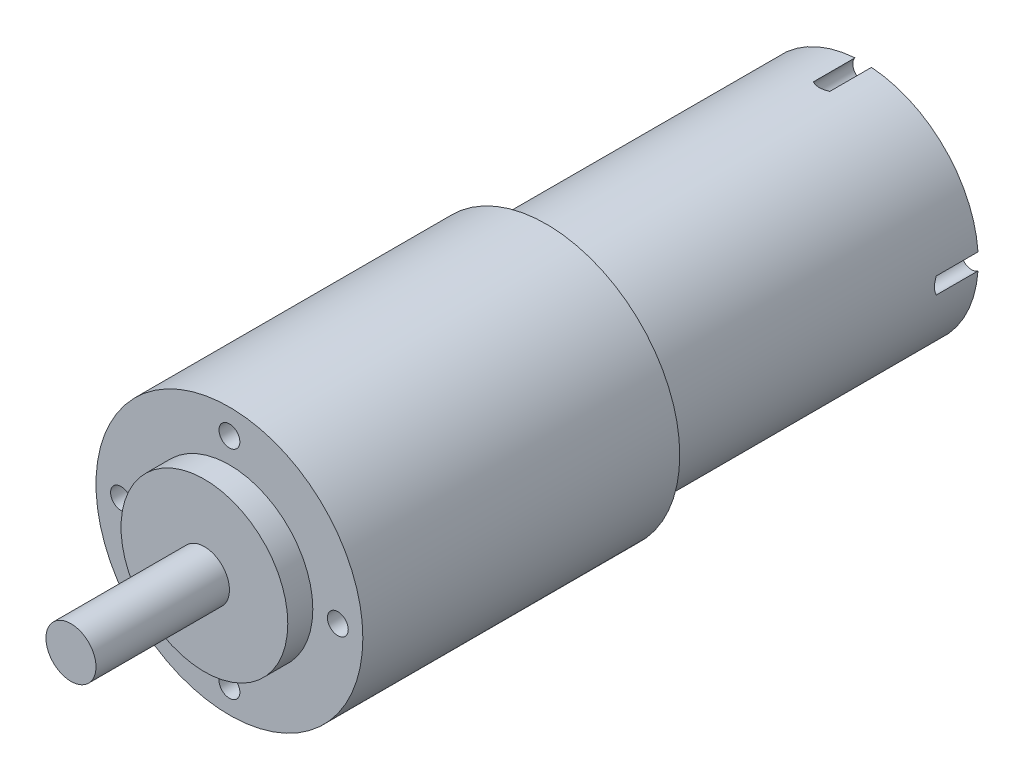
SolidWorks part; units mm, degrees
ref_plane "Front Plane" through (0, 0, 0) normal (0, 0, 1) x (1, 0, 0)
ref_plane "Top Plane" through (0, 0, 0) normal (0, 1, 0) x (1, 0, 0)
ref_plane "Right Plane" through (0, 0, 0) normal (1, 0, 0) x (0, 0, -1)
sketch "Sketch1" plane through (0, 0, 0) normal (0, 0, 1) x (1, 0, 0)
  circle A0 centre (0, 0) radius 16
  dimension "D1" = 32
extrude "Boss-Extrude1" add sketch "Sketch1" along normal blind 38 contours A0
sketch "Sketch2" plane through (0, 0, 0) normal (0, 0, -1) x (-1, 0, 0)
  circle A0 centre (0, 0) radius 13.8
  dimension "D1" = 27.6
extrude "Boss-Extrude2" add sketch "Sketch2" along normal blind 38 contours A0
sketch "Sketch3" plane through (0, 0, -38) normal (0, 0, -1) x (-1, 0, 0)
  circle A0 centre (0, 0) radius 5
  dimension "D1" = 10
extrude "Boss-Extrude3" add sketch "Sketch3" along normal blind 2
sketch "Sketch4" plane through (0, 0, 38) normal (0, 0, 1) x (1, 0, 0)
  circle A0 centre (0, 0) radius 10
  dimension "D1" = 20
extrude "Boss-Extrude4" add sketch "Sketch4" along normal blind 3
sketch "Sketch5" plane through (0, 0, 41) normal (0, 0, 1) x (1, 0, 0)
  circle A0 centre (0, 0) radius 3
  dimension "D1" = 6
extrude "Boss-Extrude5" add sketch "Sketch5" along normal blind 16
sketch "Sketch6" plane through (0, 0, -38) normal (0, 0, -1) x (-1, 0, 0)
  circle A0 centre (0, 0) radius 13
  dimension "D1" = 26
hole_wizard "Tap Drill for M3 Tap1" positions "Sketch7" profile "Sketch8" hole size "M3" standard "ISO"
sketch "Sketch7" plane through (0, 0, -38) normal (0, 0, -1) x (-1, 0, 0)
  circle A0 centre (0, 0) radius 13 construction
  point P0 (-13, 0)
  point P4 (0, -13)
  point P6 (13, 0)
  point P8 (0, 13)
sketch "Sketch8" plane through (13, 0, -38) normal (1, 0, 0) x (0, 1, 0)
  line L0 (0, 0) -> (0, 5.7511)
  line L1 (0, 5.7511) -> (1.25, 5)
  line L2 (1.25, 5) -> (1.25, 0)
  line L5 (1.25, 0) -> (0, 0)
  line L10 (0, 5.7511) -> (-1.25, 5) construction
  line L11 (0, -6.35) -> (0, 107.95) construction
  dimension "Hole Dia." = 2.5
  dimension "Hole Depth" = 5
  dimension "Drill Angle" = 118
sketch "Sketch9" plane through (0, 0, 38) normal (0, 0, 1) x (1, 0, 0)
  circle A0 centre (0, 0) radius 13
  dimension "D1" = 26
hole_wizard "Tap Drill for M3 Tap2" positions "Sketch10" profile "Sketch11" hole size "M3" standard "ISO"
sketch "Sketch10" plane through (0, 0, 38) normal (0, 0, 1) x (1, 0, 0)
  circle A0 centre (0, 0) radius 13 construction
  point P0 (0, 13)
  point P4 (-13, 0)
  point P6 (0, -13)
  point P8 (13, 0)
sketch "Sketch11" plane through (0, 13, 38) normal (1, 0, 0) x (0, -1, 0)
  line L0 (0, 0) -> (0, 5.7511)
  line L1 (0, 5.7511) -> (1.25, 5)
  line L2 (1.25, 5) -> (1.25, 0)
  line L5 (1.25, 0) -> (0, 0)
  line L10 (0, 5.7511) -> (-1.25, 5) construction
  line L11 (0, -6.35) -> (0, 107.95) construction
  dimension "Hole Dia." = 2.5
  dimension "Hole Depth" = 5
  dimension "Drill Angle" = 118
